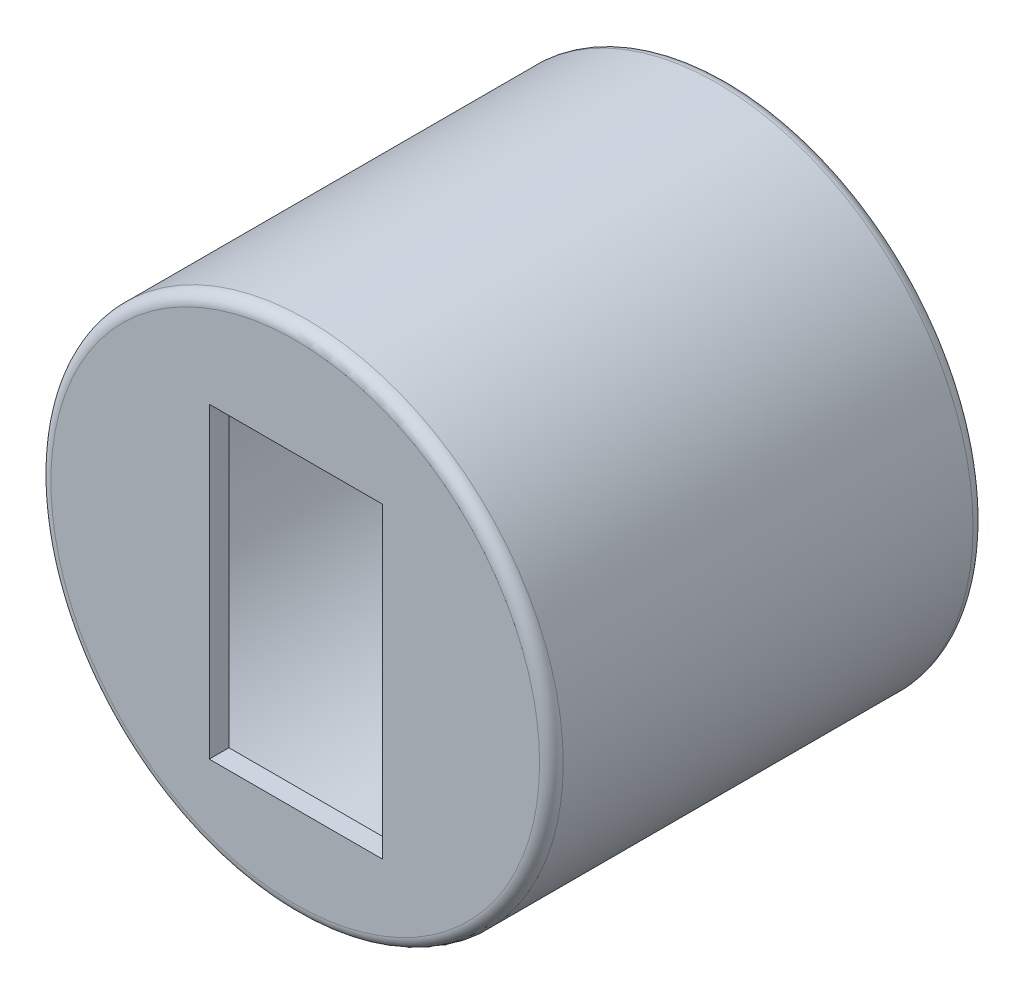
SolidWorks part; units mm, degrees
ref_plane "Front Plane" through (0, 0, 0) normal (0, 0, 1) x (1, 0, 0)
ref_plane "Top Plane" through (0, 0, 0) normal (0, 1, 0) x (1, 0, 0)
ref_plane "Right Plane" through (0, 0, 0) normal (1, 0, 0) x (0, 0, -1)
sketch "Sketch1" plane through (0, 0, 0) normal (0, 0, 1) x (1, 0, 0)
  circle A0 centre (0, 0) radius 6
  circle A1 centre (0, 0) radius 6.5
  dimension "D1" = 12
  dimension "D2" = 0.5
extrude "Boss-Extrude1" add sketch "Sketch1" along normal blind 10
sketch "Sketch2" plane through (0, 0, 0) normal (0, 0, -1) x (-1, 0, 0)
  circle A2 centre (0, 0) radius 6.5
extrude "Boss-Extrude2" add sketch "Sketch2" along normal blind 0.5
sketch "Sketch3" plane through (0, 0, 10) normal (0, 0, 1) x (1, 0, 0)
  line L0 (-2.1819, 3.7) -> (-2.1819, -4.1)
  line L5 (-4.3806, 4.7507) -> (4.0674, -4.411) construction
  line L6 (-2.1819, -4.1) -> (2.1819, 4.1) construction
  line L7 (2.2181, 3.7) -> (2.2181, -4.1)
  line L8 (2.2181, -4.1) -> (-2.1819, -4.1)
  line L9 (-2.1819, 3.7) -> (2.2181, 3.7)
  line L10 (0, -6.5) -> (0, 6.5) construction
  line L11 (-2.1819, -4.1) -> (2.2181, -4.1) construction
  line L12 (-6, 0) -> (6, 0) construction
  circle A0 centre (0, 0) radius 6.5
  circle A1 centre (0, 0) radius 6 construction
  circle A3 centre (0, 0) radius 6 construction
  point P17 (0, 0)
  dimension "D2" = 7.8
  dimension "D3" = 4.4
  dimension "D4" = 4.4
extrude "Boss-Extrude3" add sketch "Sketch3" along normal blind 0.5
sketch "Sketch4" plane through (0, 0, -0.5) normal (0, 0, -1) x (-1, 0, 0)
  line L1 (-1.45, 1.8) -> (1.45, 1.8)
  line L2 (-1.45, 1.8) -> (-1.45, -1.8)
  line L3 (-1.45, -1.8) -> (1.45, -1.8)
  line L4 (1.45, 1.8) -> (1.45, -1.8)
  line L5 (-1.45, 1.8) -> (1.45, -1.8) construction
  line L6 (-1.45, -1.8) -> (1.45, 1.8) construction
  point P0 (0, 0)
  dimension "D1" = 3.6
  dimension "D2" = 2.9
extrude "Cut-Extrude1" cut sketch "Sketch4" against normal blind 1
fillet "Fillet1" radius 0.1 4 edges at (-1.45, -1.8, -0.25) (1.45, -1.8, -0.25) (1.45, 1.8, -0.25) (-1.45, 1.8, -0.25)
fillet "Fillet2" radius 0.3 2 edges at (-6.5, 0, -0.5) (6.5, 0, 10.5)
